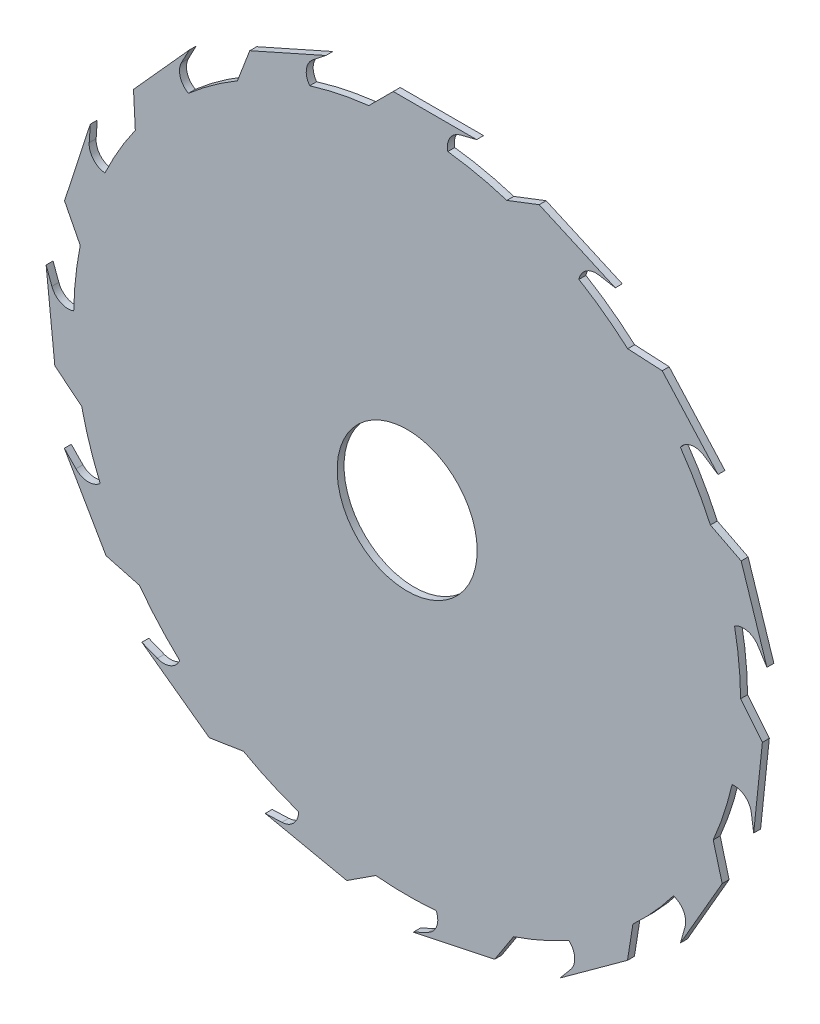
SolidWorks part; units mm, degrees
ref_plane "Front Plane" through (0, 0, 0) normal (0, 0, 1) x (1, 0, 0)
ref_plane "Top Plane" through (0, 0, 0) normal (0, 1, 0) x (1, 0, 0)
ref_plane "Right Plane" through (0, 0, 0) normal (1, 0, 0) x (0, 0, -1)
sketch "Sketch1" plane through (0, 0, 0) normal (0, 0, 1) x (1, 0, 0)
  circle A0 centre (0, 0) radius 76.2
  dimension "D1" = 152.4
extrude "Boss-Extrude1" add sketch "Sketch1" along normal blind 1.5875 contours A0
sketch "Sketch2" plane through (0, 0, 1.5875) normal (0, 0, 1) x (1, 0, 0)
  circle A0 centre (0, 0) radius 16.002
  dimension "D1" = 32.004
extrude "Cut-Extrude1" cut sketch "Sketch2" against normal up to next
sketch "Sketch4" plane through (0, 0, 1.5875) normal (0, 0, 1) x (1, 0, 0)
  line L0 (-9.525, 74.93) -> (-3.175, 81.28)
  line L1 (-3.175, 81.28) -> (15.875, 81.28)
  line L2 (15.875, 81.28) -> (12.1813, 80.3459)
  line L3 (9.525, 74.93) -> (-9.525, 74.93)
  arc A0 (12.1813, 80.3459) -> (9.525, 74.93) centre (13.1512, 76.5108) ccw
  point P8 (0, 74.93)
  dimension "D1" = 3.81
  dimension "D7" = 1.5808
  dimension "D2" = 19.05
  dimension "D3" = 6.35
  dimension "D4" = 19.05
  dimension "D5" = 81.28
  dimension "D6" = 45
extrude "Boss-Extrude2" add sketch "Sketch4" against normal up to surface (1.5875 mm away) up to face at (16.002, 0, 0)
pattern_circular "CirPattern1" count 15 over 360 about axis through (0, 0, 0) along (0, 0, 1) of "Boss-Extrude2"
